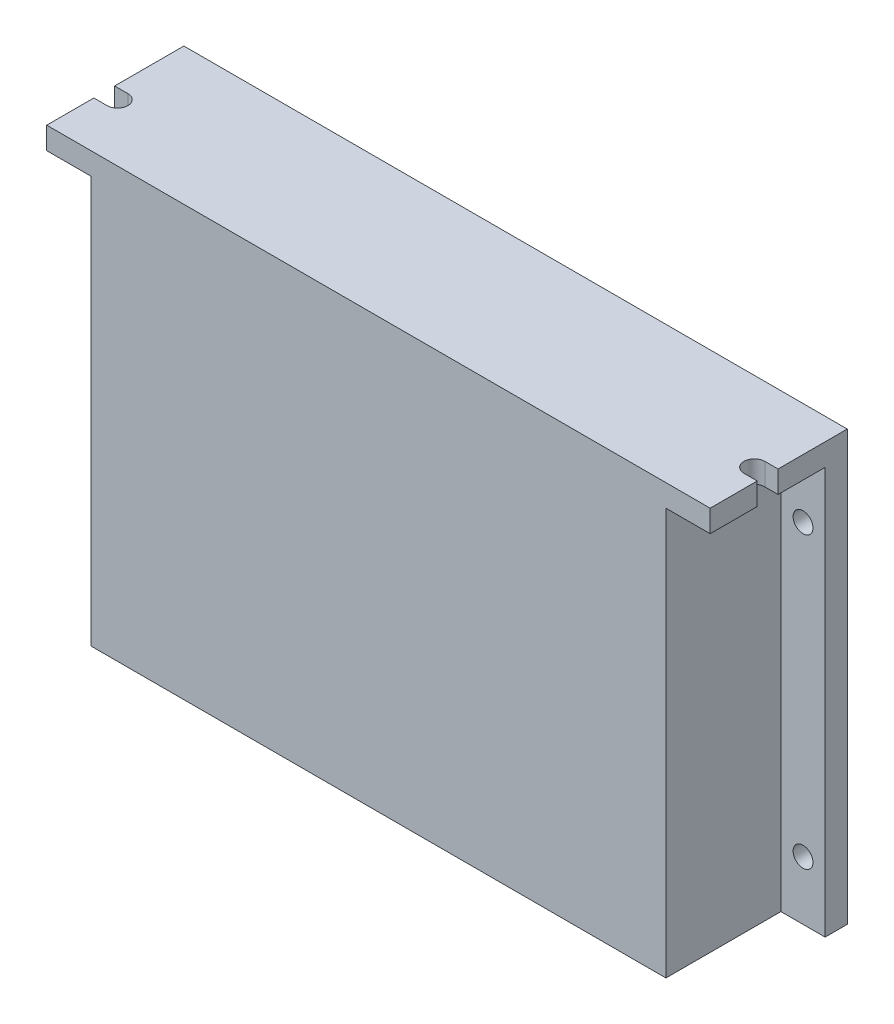
SolidWorks part; units mm, degrees
ref_plane "前视基准面" through (0, 0, 0) normal (0, 0, 1) x (1, 0, 0)
ref_plane "上视基准面" through (0, 0, 0) normal (0, 1, 0) x (1, 0, 0)
ref_plane "右视基准面" through (0, 0, 0) normal (1, 0, 0) x (0, 0, -1)
sketch "草图1" plane through (0, 0, 0) normal (0, 1, 0) x (1, 0, 0)
  line L1 (-75, -15.5) -> (75, -15.5)
  line L2 (-75, -15.5) -> (-75, 15.5)
  line L3 (-75, 15.5) -> (75, 15.5)
  line L4 (75, -15.5) -> (75, 15.5)
  line L5 (-75, -15.5) -> (75, 15.5) construction
  line L6 (-75, 15.5) -> (75, -15.5) construction
  point P0 (0, 0)
  dimension "D1" = 150
  dimension "D2" = 31
extrude "凸台-拉伸1" add sketch "草图1" along normal blind 97
sketch "草图2" plane through (0, 0, 15.5) normal (0, 0, 1) x (1, 0, 0)
  line L0 (-75, 0) -> (75, 0) construction
  line L1 (75, 97) -> (75, 0) construction
  line L2 (-75, 13.15) -> (-72, 13.15) construction
  line L3 (-75, 15.5) -> (-72, 15.5)
  line L4 (-75, 10.8) -> (-72, 10.8)
  line L5 (-75, 97) -> (-75, 0) construction
  line L6 (-75, 78.85) -> (-72, 78.85) construction
  line L7 (-75, 81.2) -> (-72, 81.2)
  line L8 (-75, 76.5) -> (-72, 76.5)
  circle A0 centre (70, 13.25) radius 2.25
  circle A1 centre (70, 78.75) radius 2.25
  arc A3 (-75, 15.5) -> (-75, 10.8) centre (-75, 13.15) ccw
  arc A4 (-72, 10.8) -> (-72, 15.5) centre (-72, 13.15) ccw
  arc A5 (-75, 81.2) -> (-75, 76.5) centre (-75, 78.85) ccw
  arc A6 (-72, 76.5) -> (-72, 81.2) centre (-72, 78.85) ccw
  point P10 (-73.5, 13.15)
  point P15 (0, 0)
  point P20 (-73.5, 78.85)
  point P25 (0, 0)
  dimension "D1" = 4.5
  dimension "D3" = 4.5
  dimension "D6" = 2.35
  dimension "D10" = 2.35
  dimension "D2" = 13.25
  dimension "D4" = 78.75
  dimension "D5" = 5
  dimension "D7" = 3
  dimension "D8" = 10.8
  dimension "D9" = 76.5
  dimension "D11" = 3
extrude "切除-拉伸1" cut sketch "草图2" against normal through all
sketch "草图3" plane through (0, 0, 15.5) normal (0, 0, 1) x (1, 0, 0)
  line L0 (0, 0) -> (0, 74.7436) construction
  line L1 (-75, 0) -> (-65, 0)
  line L2 (-75, 0) -> (-75, 92)
  line L3 (-75, 92) -> (-65, 92)
  line L4 (-65, 0) -> (-65, 92)
  line L5 (-75, 97) -> (75, 97) construction
  dimension "D1" = 10
  dimension "D2" = 5
extrude "切除-拉伸2" cut sketch "草图3" against normal offset from surface (26 mm away) 5 up to face at (72.25, 78.75, -15.5)
mirror "镜向1" about plane through (0, 0, 0) normal (1, 0, 0) of "切除-拉伸2"
sketch "草图4" plane through (0, 92, 0) normal (0, -1, 0) x (1, 0, 0)
  line L0 (-75, 2.5) -> (-72, 2.5) construction
  line L1 (-75, -10.5) -> (-75, 15.5) construction
  line L2 (-75, 4.85) -> (-72, 4.85)
  line L3 (-75, 0.15) -> (-72, 0.15)
  arc A0 (-75, 4.85) -> (-75, 0.15) centre (-75, 2.5) ccw
  arc A1 (-72, 0.15) -> (-72, 4.85) centre (-72, 2.5) ccw
  point P4 (-73.5, 2.5)
  dimension "D1" = 2.35
  dimension "D2" = 3
extrude "切除-拉伸3" cut sketch "草图4" against normal up to surface (5 mm away) up to face at (0, 97, 0)
mirror "镜向2" about plane through (0, 0, 0) normal (1, 0, 0) of "切除-拉伸3"
